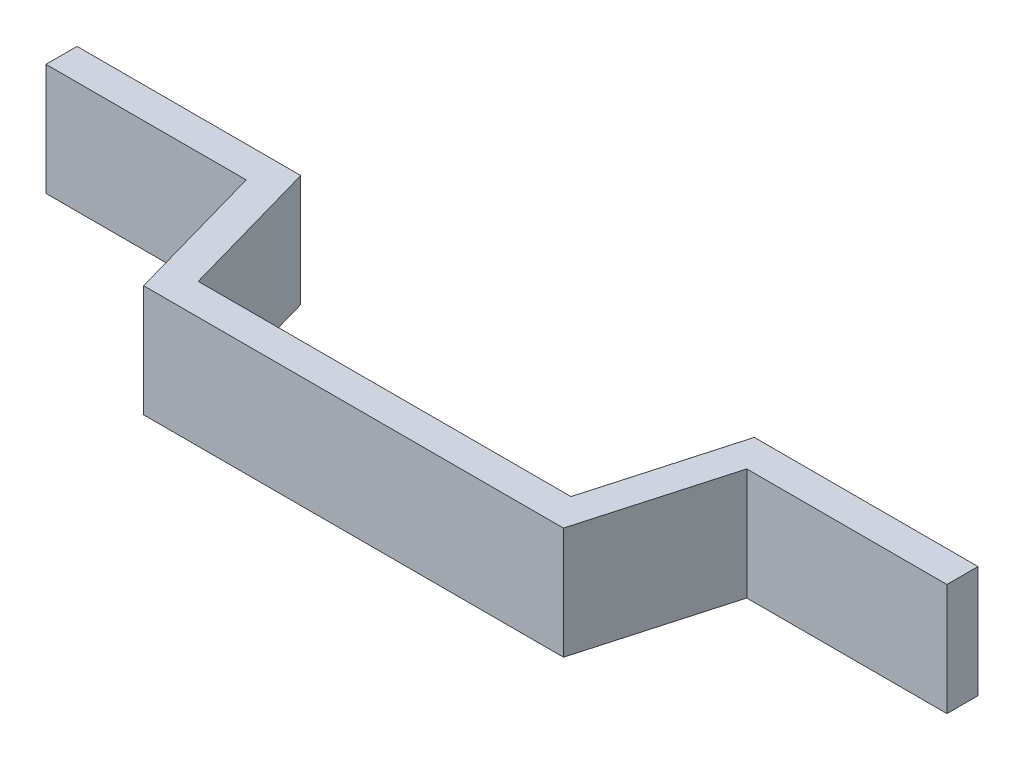
SolidWorks part; units mm, degrees
ref_plane "前视基准面" through (0, 0, 0) normal (0, 0, 1) x (1, 0, 0)
ref_plane "上视基准面" through (0, 0, 0) normal (0, 1, 0) x (1, 0, 0)
ref_plane "右视基准面" through (0, 0, 0) normal (1, 0, 0) x (0, 0, -1)
sketch "草图1" plane through (0, 0, 0) normal (0, 1, 0) x (1, 0, 0)
  line L0 (-72.5, 28) -> (-36.5, 28)
  line L1 (-36.5, 28) -> (-30, 5)
  line L2 (-30, 5) -> (30, 5)
  line L3 (30, 5) -> (36.5, 28)
  line L4 (36.5, 28) -> (72.5, 28)
  line L5 (72.5, 28) -> (72.5, 23)
  line L6 (72.5, 23) -> (40.2828, 23)
  line L7 (40.2828, 23) -> (33.7828, 0)
  line L8 (33.7828, 0) -> (-33.7828, 0)
  line L9 (-33.7828, 0) -> (-40.2828, 23)
  line L10 (-40.2828, 23) -> (-72.5, 23)
  line L11 (-72.5, 23) -> (-72.5, 28)
  point P2 (0, 0)
  dimension "D1" = 60
  dimension "D2" = 36
  dimension "D3" = 23
  dimension "D4" = 5
  dimension "D5" = 5
  dimension "D6" = 5
  dimension "D7" = 5
  dimension "D8" = 145
extrude "凸台-拉伸1" add sketch "草图1" along normal blind 18
sketch "草图2" plane through (0, 0, 0) normal (0, 1, 0) x (1, 0, 0)
  line L0 (-33.7828, 0) -> (33.7828, 0) construction
  line L1 (-38.5, 28) -> (38.5, 28)
  line L2 (-38.5, 28) -> (-38.5, 0)
  line L3 (-38.5, 0) -> (38.5, 0)
  line L4 (38.5, 28) -> (38.5, 0)
  point P4 (0, 0)
  dimension "D1" = 77
  dimension "D2" = 28
